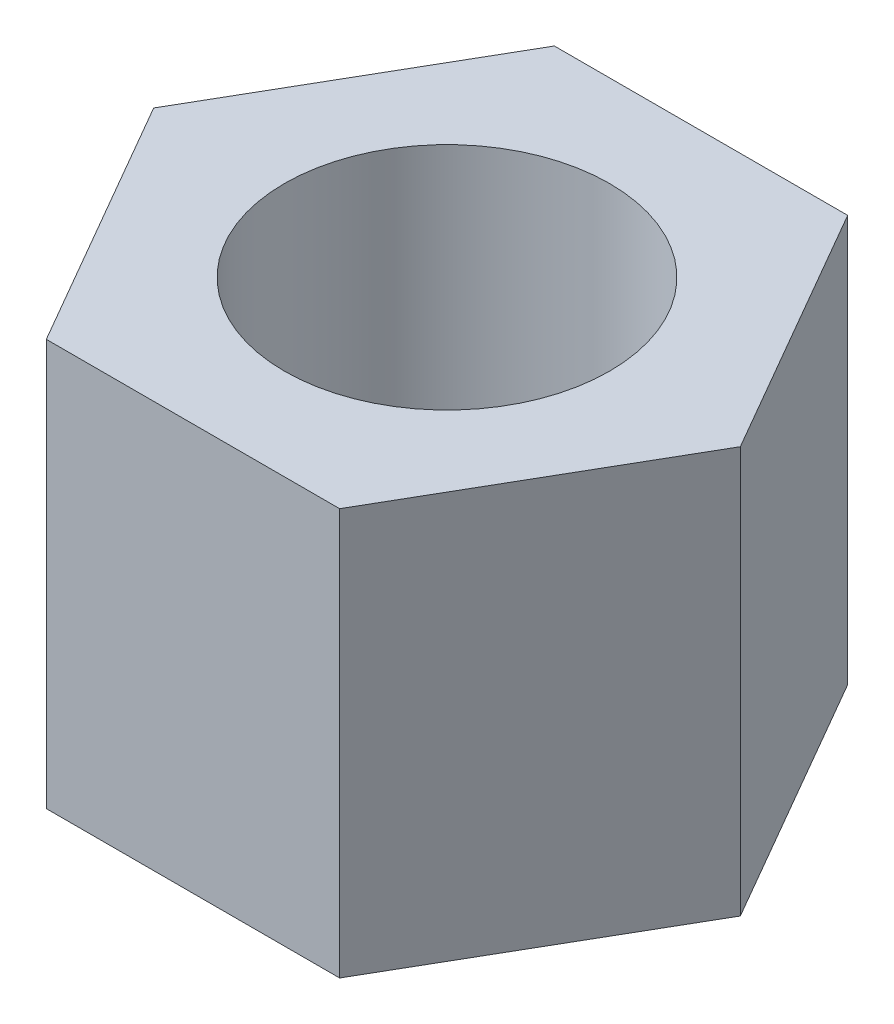
SolidWorks part; units mm, degrees
material "黄铜"
ref_plane "前视基准面" through (0, 0, 0) normal (0, 0, 1) x (1, 0, 0)
ref_plane "上视基准面" through (0, 0, 0) normal (0, 1, 0) x (1, 0, 0)
ref_plane "右视基准面" through (0, 0, 0) normal (1, 0, 0) x (0, 0, -1)
other "Configuration Table"
sketch "草图1" plane through (0, 0, 0) normal (0, 1, 0) x (1, 0, 0)
  line L1 (2.8868, 0) -> (1.4434, 2.5)
  line L2 (1.4434, 2.5) -> (-1.4434, 2.5)
  line L3 (-1.4434, 2.5) -> (-2.8868, 0)
  line L4 (-2.8868, 0) -> (-1.4434, -2.5)
  line L5 (-1.4434, -2.5) -> (1.4434, -2.5)
  line L6 (1.4434, -2.5) -> (2.8868, 0)
  circle A0 centre (0, 0) radius 1.6
  circle A1 centre (0, 0) radius 2.5 construction
  dimension "D1" = 3.2
  dimension "D2" = 5
extrude "凸台-拉伸1" add sketch "草图1" along normal mid plane 4
